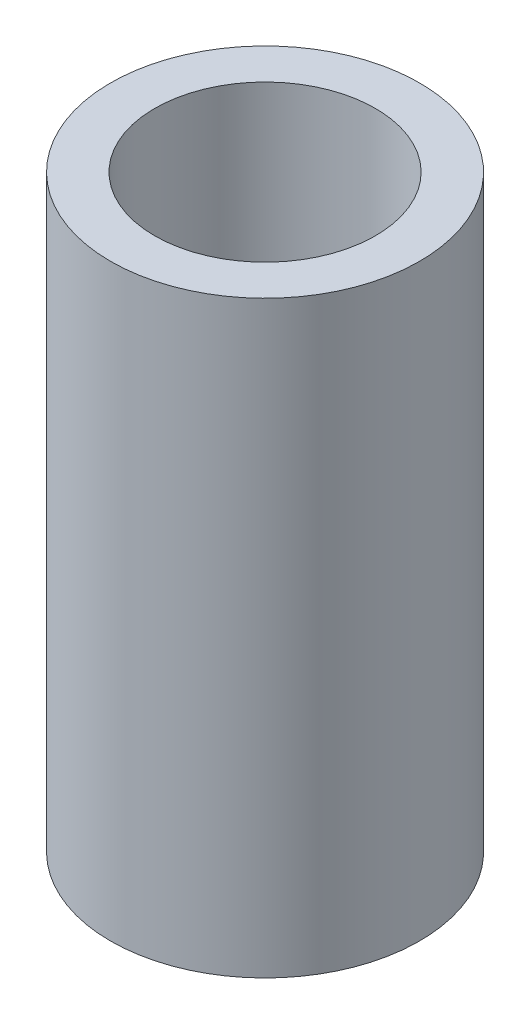
SolidWorks part; units mm, degrees
material "黄铜"
ref_plane "前视基准面" through (0, 0, 0) normal (0, 0, 1) x (1, 0, 0)
ref_plane "上视基准面" through (0, 0, 0) normal (0, 1, 0) x (1, 0, 0)
ref_plane "右视基准面" through (0, 0, 0) normal (1, 0, 0) x (0, 0, -1)
other "Configuration Table"
sketch "草图1" plane through (0, 0, 0) normal (0, 1, 0) x (1, 0, 0)
  circle A0 centre (0, 0) radius 2.1
  circle A1 centre (0, 0) radius 1.5
  dimension "D1" = 4.2
  dimension "D2" = 3
extrude "凸台-拉伸1" add sketch "草图1" along normal mid plane 8
